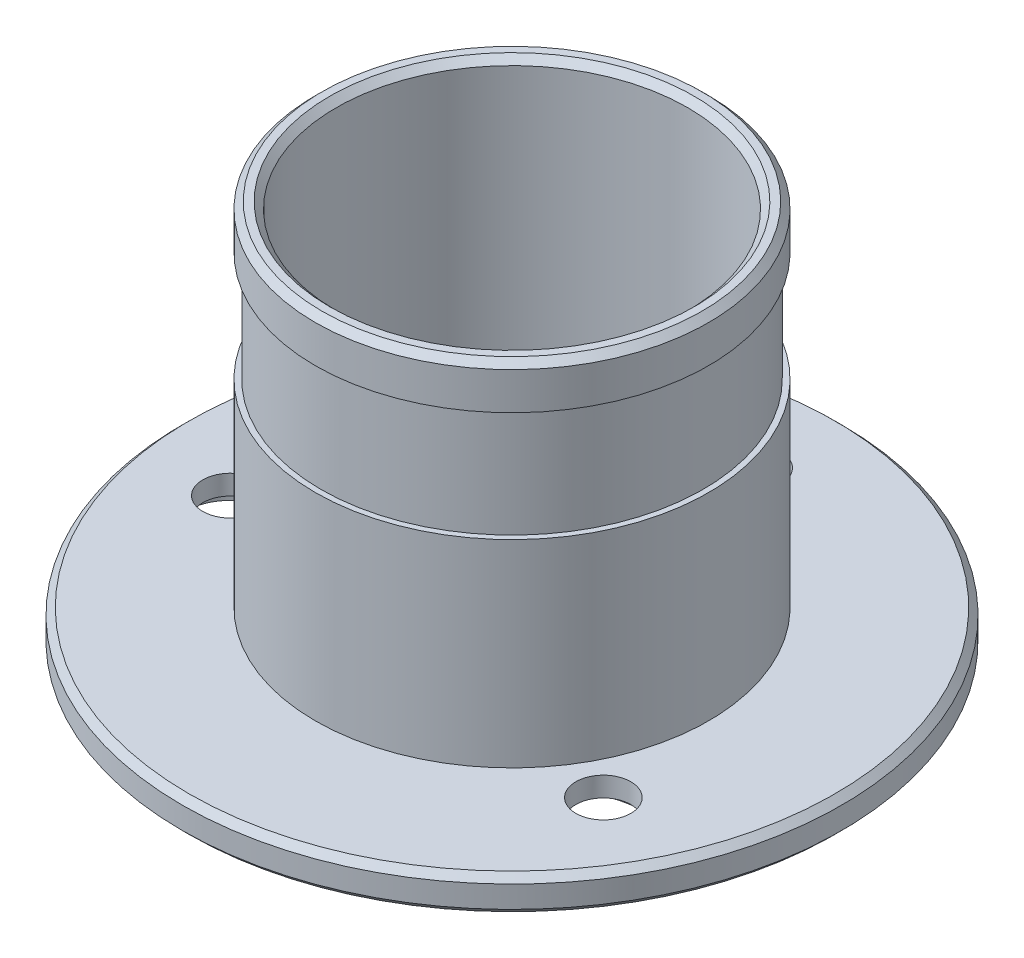
SolidWorks part; units mm, degrees
material "尼龙"
ref_plane "前视" through (0, 0, 0) normal (0, 0, 1) x (1, 0, 0)
ref_plane "上视" through (0, 0, 0) normal (0, 1, 0) x (1, 0, 0)
ref_plane "右视" through (0, 0, 0) normal (1, 0, 0) x (0, 0, -1)
sketch "草图1" plane through (0, 0, 0) normal (0, 1, 0) x (1, 0, 0)
  circle A0 centre (0, 0) radius 15
  dimension "D1" = 30
extrude "凸台-拉伸1" add sketch "草图1" along normal blind 1.6
sketch "草图2" plane through (0, 1.6, 0) normal (0, 1, 0) x (1, 0, 0)
  circle A0 centre (0, 0) radius 8.95
  dimension "D1" = 17.9
extrude "凸台-拉伸2" add sketch "草图2" along normal blind 16
sketch "草图3" plane through (0, 0, 0) normal (0, -1, 0) x (-1, 0, 0)
  circle A0 centre (0, 0) radius 8
  dimension "D1" = 16
extrude "切除-拉伸1" cut sketch "草图3" against normal through all
fillet "圆角1" radius 2 1 edges at (0, 0, -8)
hole_wizard "大小mm 暗销孔1" positions "草图4" profile "草图5" hole size "Ø2.5" standard "GB" end condition through all
sketch "草图4" plane through (0, 1.6, 0) normal (0, 1, 0) x (1, 0, 0)
  line L0 (0, 0) -> (0, 11) construction
  line L2 (23.2708, 0) -> (-22.7038, 0) construction
  line L4 (-10.8158, -2.0046) -> (0, 0) construction
  line L5 (0, 0) -> (9.5739, -5.4167) construction
  point P0 (0, 11)
  point P6 (9.5739, -5.4167)
  point P8 (-10.8158, -2.0046)
  dimension "D1" = 11
  dimension "D2" = 29.5
  dimension "D3" = 10.5
  dimension "D4" = 11
  dimension "D5" = 11
sketch "草图5" plane through (0, 1.6, -11) normal (1, 0, 0) x (0, 0, 1)
  line L0 (0, 0) -> (0, 1.6)
  line L1 (0, 1.6) -> (1.25, 1.6)
  line L2 (1.25, 1.6) -> (1.25, 0)
  line L5 (1.25, 0) -> (0, 0)
  line L11 (0, -6.35) -> (0, 107.95) construction
  dimension "通孔孔直径" = 2.5
  dimension "通孔孔深度" = 1.6
sketch "草图6" plane through (0, 0, 0) normal (0, -1, 0) x (-1, 0, 0)
  circle A0 centre (0, 11) radius 2
  circle A1 centre (10.8158, -2.0046) radius 2
  circle A2 centre (-9.5739, -5.4167) radius 2
  dimension "D1" = 4
  dimension "D2" = 4
  dimension "D3" = 4
extrude "切除-拉伸2" cut sketch "草图6" against normal blind 0.7
sketch "草图7" plane through (0, 17.6, 0) normal (0, 1, 0) x (1, 0, 0)
  circle A0 centre (0, 0) radius 8.7
  circle A2 centre (0, 0) radius 8.95
  dimension "D1" = 17.4
  dimension "D2" = 17.9
extrude "切除-拉伸3" cut sketch "草图7" against normal blind 5 from offset 2 offset against normal yes
chamfer "倒角1" distance 0.3 angle 45 4 edges at (0, 0, 15) (0, 1.6, 15) (0, 17.6, -8) (0, 17.6, 8.95)
